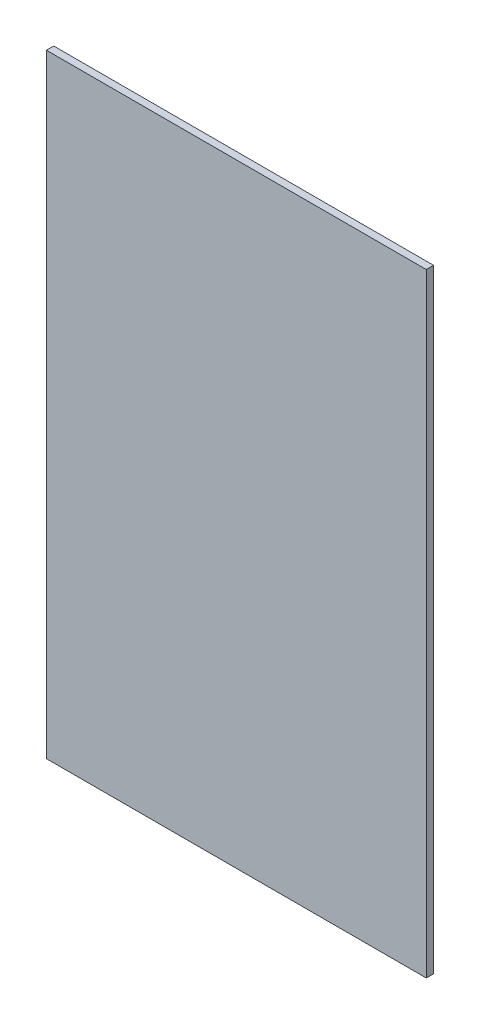
SolidWorks part; units mm, degrees
ref_plane "Front Plane" through (0, 0, 0) normal (0, 0, 1) x (1, 0, 0)
ref_plane "Top Plane" through (0, 0, 0) normal (0, 1, 0) x (1, 0, 0)
ref_plane "Right Plane" through (0, 0, 0) normal (1, 0, 0) x (0, 0, -1)
sketch "Sketch1" plane through (0, 0, 0) normal (0, 0, 1) x (1, 0, 0)
  line L1 (-18.2267, 48.3647) -> (311.9733, 48.3647)
  line L2 (-18.2267, 48.3647) -> (-18.2267, -485.0353)
  line L3 (-18.2267, -485.0353) -> (311.9733, -485.0353)
  line L4 (311.9733, 48.3647) -> (311.9733, -485.0353)
  dimension "D1" = 330.2
  dimension "D2" = 533.4
extrude "Boss-Extrude1" add sketch "Sketch1" along normal blind 6.35
